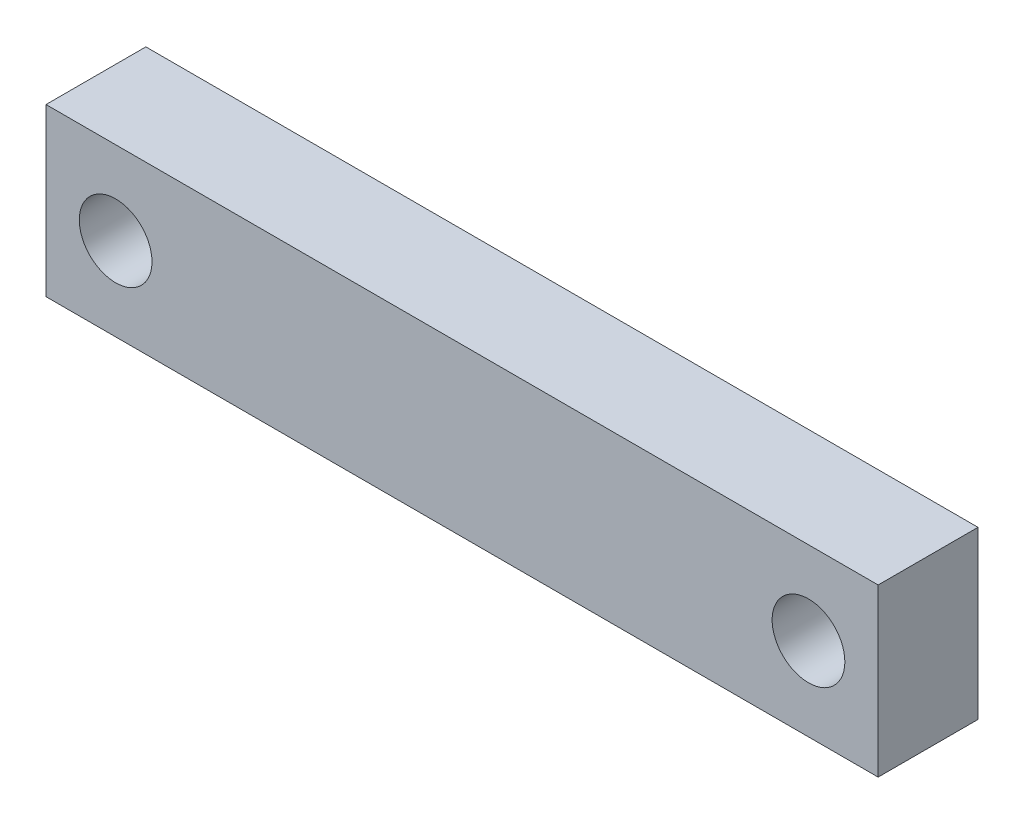
SolidWorks part; units mm, degrees
ref_plane "Front Plane" through (0, 0, 0) normal (0, 0, 1) x (1, 0, 0)
ref_plane "Top Plane" through (0, 0, 0) normal (0, 1, 0) x (1, 0, 0)
ref_plane "Right Plane" through (0, 0, 0) normal (1, 0, 0) x (0, 0, -1)
sketch "Sketch2" plane through (0, 0, 0) normal (0, 0, 1) x (1, 0, 0)
  line L1 (-12.5, -2.5) -> (12.5, -2.5)
  line L2 (-12.5, -2.5) -> (-12.5, 2.5)
  line L3 (-12.5, 2.5) -> (12.5, 2.5)
  line L4 (12.5, -2.5) -> (12.5, 2.5)
  line L5 (-12.5, -2.5) -> (12.5, 2.5) construction
  line L6 (-12.5, 2.5) -> (12.5, -2.5) construction
  point P0 (0, 0)
  dimension "D1" = 25
  dimension "D2" = 5
extrude "Boss-Extrude1" add sketch "Sketch2" along normal blind 3
sketch "Sketch3" plane through (0, 0, 3) normal (0, 0, 1) x (1, 0, 0)
  line L0 (12.5, 2.5) -> (-12.5, 2.5) construction
  line L1 (-12.5, 2.5) -> (-12.5, -2.5) construction
  point P0 (-10.4078, 0)
  point P1 (10.4078, 0)
  dimension "D1" = 2.5
  dimension "D2" = 20.8156
  dimension "D3" = 2.0922
hole_wizard "#44 (0.086) Diameter Hole1" positions "3DSketch1" profile "Sketch4" hole size "#44" standard "ANSI Inch" end condition through all
sketch3d "3DSketch1"
  point P0 (-10.4078, 0, 3)
  point P3 (10.4078, 0, 3)
sketch "Sketch4" plane through (-10.4078, 0, 3) normal (1, 0, 0) x (0, -1, 0)
  line L0 (0, 0) -> (0, 3)
  line L1 (0, 3) -> (1.0922, 3)
  line L2 (1.0922, 3) -> (1.0922, 0)
  line L5 (1.0922, 0) -> (0, 0)
  line L11 (0, -6.35) -> (0, 107.95) construction
  dimension "Thru Hole Dia." = 2.1844
  dimension "Thru Hole Depth" = 3
